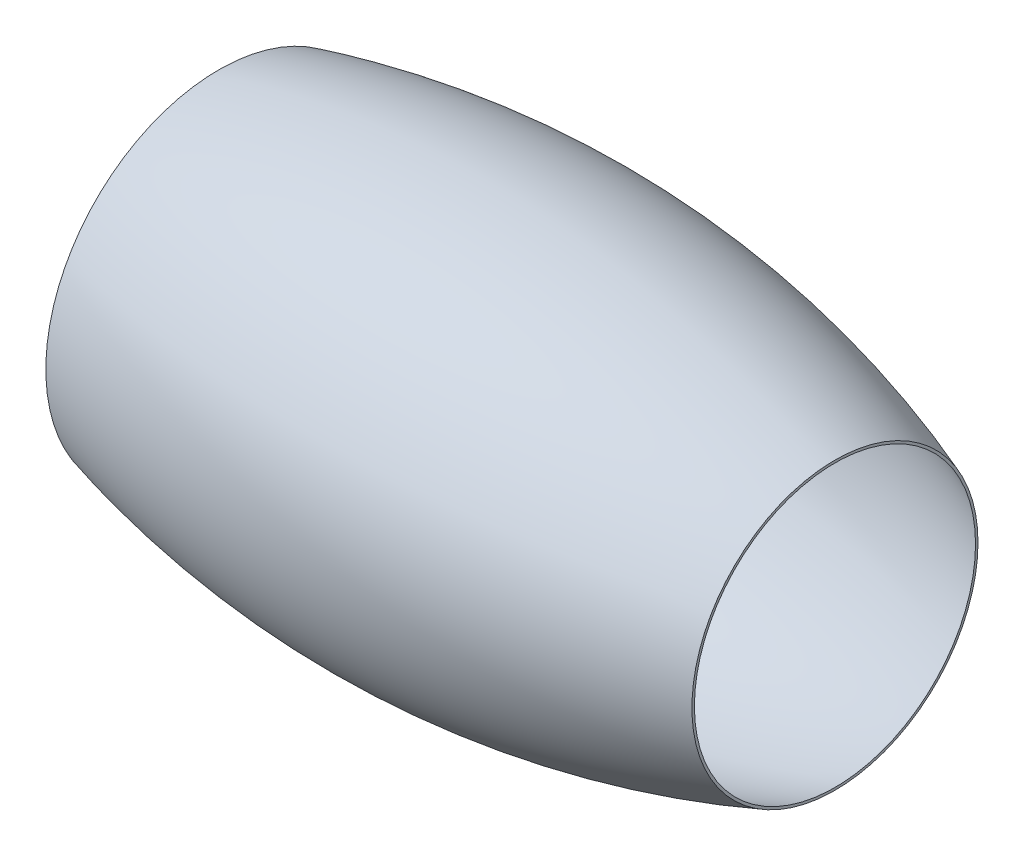
SolidWorks part; units mm, degrees
ref_plane "Front Plane" through (0, 0, 0) normal (0, 0, 1) x (1, 0, 0)
ref_plane "Top Plane" through (0, 0, 0) normal (0, 1, 0) x (1, 0, 0)
ref_plane "Right Plane" through (0, 0, 0) normal (1, 0, 0) x (0, 0, -1)
sketch "Sketch1" plane through (0, 0, 0) normal (0, 0, 1) x (1, 0, 0)
  line L0 (135.5973, 0) -> (-135.5973, 0) construction
  line L1 (0, 0) -> (0, 260) construction
  line L2 (0, 260) -> (-4.3999, 276.4207) construction
  line L3 (-4.7882, 277.8696) -> (-1.8904, 278.6461)
  line L4 (-1.8904, 278.6461) -> (-1.1139, 275.7483)
  line L5 (-1.1139, 275.7483) -> (-4.0117, 274.9719)
  line L6 (-4.0117, 274.9719) -> (-4.3999, 276.4207)
  line L7 (-5.1764, 279.3185) -> (-4.7882, 277.8696)
  line L8 (-4.7882, 277.8696) -> (-20.8763, 337.9112) construction
  line L9 (0, 243) -> (0, 240)
  line L10 (989.8236, 230.99) -> (989.8236, 226.99)
  arc A0 (0, 240) -> (-5.1764, 279.3185) centre (0, 260) cw
  arc A1 (0, 243) -> (-4.3999, 276.4207) centre (0, 260) cw
  arc A2 (0, 240) -> (0, 280) centre (0, 260) cw construction
  arc A3 (-5.1764, 279.3185) -> (989.8236, 230.99) centre (416.0096, -1316.0192) cw
  arc A4 (0, 243) -> (0, 277) centre (0, 260) cw construction
  arc A5 (-1.1139, 275.7483) -> (989.8236, 226.99) centre (417.2237, -1316.2032) cw
  point P4 (0, 0)
  dimension "D1" = 20
  dimension "D10" = 1650
  dimension "D11" = 1646
  dimension "D2" = 260
  dimension "D3" = 15
  dimension "D5" = 3
  dimension "D6" = 3
  dimension "D7" = 1.5
  dimension "D8" = 4
  dimension "D9" = 226.99
  dimension "D12" = 995
  dimension "D4" = 3
revolve "Revolve2" add sketch "Sketch1" angle 360 about L0
